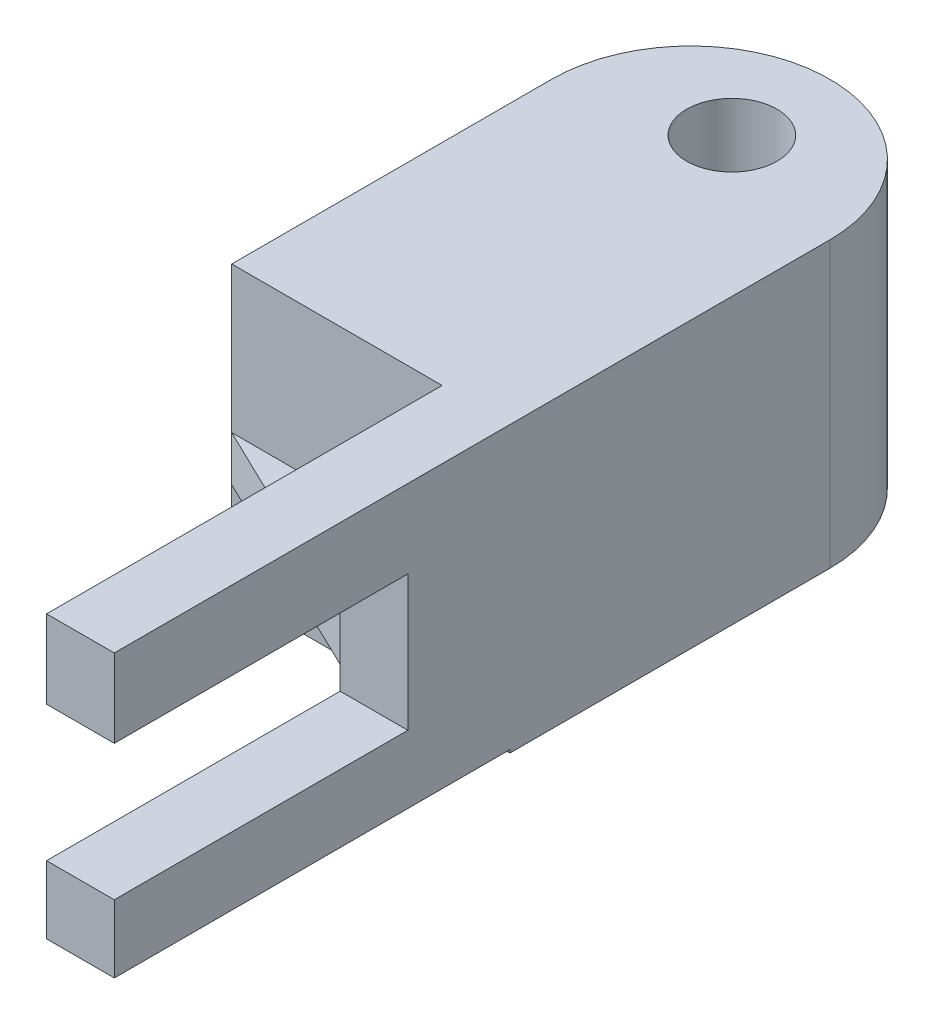
SolidWorks part; units mm, degrees
ref_plane "Front Plane" through (0, 0, 0) normal (0, 0, 1) x (1, 0, 0)
ref_plane "Top Plane" through (0, 0, 0) normal (0, 1, 0) x (1, 0, 0)
ref_plane "Right Plane" through (0, 0, 0) normal (1, 0, 0) x (0, 0, -1)
sketch "Sketch4" plane through (0, 0, 0) normal (1, 0, 0) x (0, 0, -1)
  line L0 (0, 0) -> (0, 62.3333)
  line L1 (0, 62.3333) -> (-87.5952, 62.3333)
  line L2 (-87.5952, 62.3333) -> (-87.5952, 45)
  line L3 (-87.5952, 45) -> (-22.5952, 45)
  line L4 (-22.5952, 45) -> (-22.5952, 15)
  line L5 (-22.5952, 15) -> (-87.5952, 15)
  line L6 (-87.5952, 15) -> (-87.5952, 0)
  line L7 (-87.5952, 0) -> (0, 0)
  dimension "D1" = 65
  dimension "D2" = 15
  dimension "D3" = 30
  dimension "D4" = 65
extrude "Boss-Extrude3" add sketch "Sketch4" along normal blind 15
sketch "Sketch7" plane through (0, 62.3333, 0) normal (0, 1, 0) x (1, 0, 0)
  line L0 (15, 0) -> (15, 70.8647)
  line L1 (15, 0) -> (0, 0)
  line L2 (0, 0) -> (-46.5964, 0)
  line L3 (-46.5964, 0) -> (-46.5964, 70.8647)
  arc A0 (-46.5964, 70.8647) -> (15, 70.8647) centre (-15.7982, 70.8647) cw
  point P8 (15, 60.7271)
  point P9 (15, 76.8621)
  point P10 (15, 70.8647)
extrude "Boss-Extrude6" add sketch "Sketch7" against normal blind 63
sketch "Sketch8" plane through (0, 62.3333, 0) normal (0, 1, 0) x (1, 0, 0)
  circle A0 centre (-15.9144, 80.0721) radius 10
  dimension "D1" = 20
extrude "Cut-Extrude1" cut sketch "Sketch8" against normal blind 60
ref_plane "Plane5" through (0, 20, 0) normal (0, 1, 0) x (1, 0, 0)
sketch "Sketch12" plane through (0, 20, 0) normal (0, 1, 0) x (1, 0, 0)
  line L0 (-46.5964, 0) -> (0, 0)
  line L1 (0, 0) -> (0, -22.5158)
  line L2 (0, 0) -> (0, -87.5952) construction
  line L3 (0, -22.5158) -> (-46.5964, 0)
  point P4 (0, -22.5158)
extrude "Boss-Extrude8" add sketch "Sketch12" along normal blind 10
